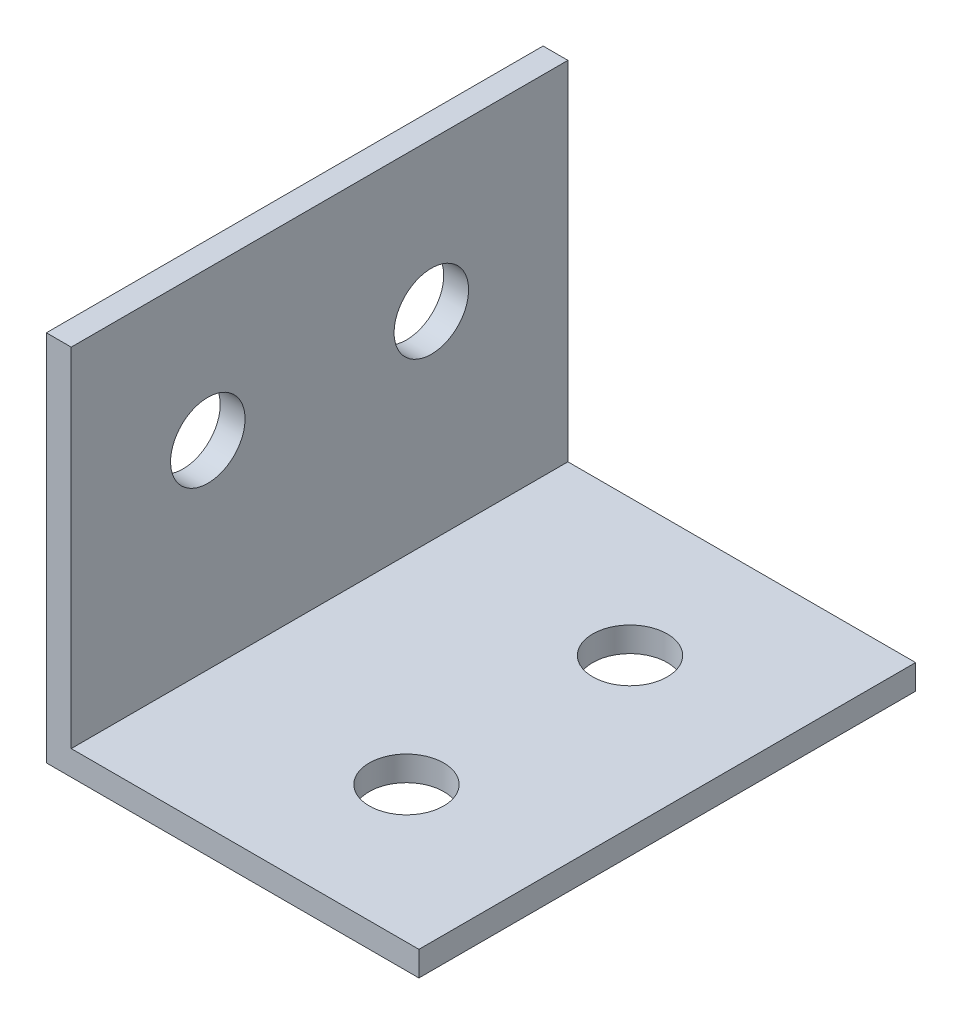
SolidWorks part; units mm, degrees
material "6061 合金"
ref_plane "前视基准面" through (0, 0, 0) normal (0, 0, 1) x (1, 0, 0)
ref_plane "上视基准面" through (0, 0, 0) normal (0, 1, 0) x (1, 0, 0)
ref_plane "右视基准面" through (0, 0, 0) normal (1, 0, 0) x (0, 0, -1)
sketch "草图1" plane through (0, 0, 0) normal (0, 0, 1) x (1, 0, 0)
  line L0 (0, 0) -> (0, 14)
  line L1 (0, 14) -> (-1, 14)
  line L2 (-1, 14) -> (-1, -1)
  line L3 (-1, -1) -> (14, -1)
  line L4 (14, -1) -> (14, 0)
  line L5 (14, 0) -> (0, 0)
  dimension "D1" = 15
  dimension "D2" = 15
  dimension "D3" = 1
extrude "凸台-拉伸1" add sketch "草图1" along normal blind 20
sketch "草图2" plane through (0, 0, 0) normal (0, 1, 0) x (1, 0, 0)
  line L0 (8, 0) -> (8, -20) construction
  line L1 (14, 0) -> (0, 0) construction
  line L2 (14, -20) -> (0, -20) construction
  line L3 (-1, -20) -> (-1, 0) construction
  line L4 (8, -10) -> (14, -10) construction
  line L5 (14, -20) -> (14, 0) construction
  circle A0 centre (8, -5.5) radius 1.5
  circle A1 centre (8, -14.5) radius 1.5
  dimension "D2" = 4.5
  dimension "D3" = 3
  dimension "D1" = 9
extrude "切除-拉伸1" cut sketch "草图2" against normal through all
ref_plane "基准面1" through (0, 0, 0) normal (-0.7071, 0.7071, 0) x (0, 0, 1)
mirror "镜向1" about plane through (0, 0, 0) normal (-0.7071, 0.7071, 0) of "切除-拉伸1"
